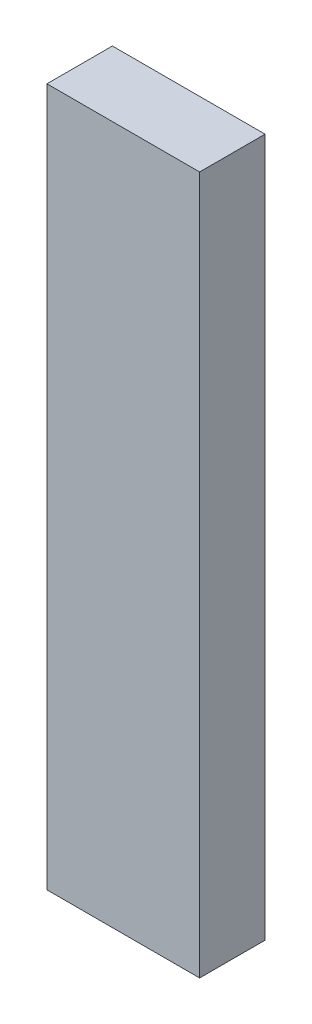
SolidWorks part; units mm, degrees
material "Pine"
ref_plane "Front Plane" through (0, 0, 0) normal (0, 0, 1) x (1, 0, 0)
ref_plane "Top Plane" through (0, 0, 0) normal (0, 1, 0) x (1, 0, 0)
ref_plane "Right Plane" through (0, 0, 0) normal (1, 0, 0) x (0, 0, -1)
sketch "Sketch1" plane through (0, 0, 0) normal (0, 1, 0) x (1, 0, 0)
  line L1 (0, 0) -> (88.9, 0)
  line L2 (0, 0) -> (0, 38.1)
  line L3 (0, 38.1) -> (88.9, 38.1)
  line L4 (88.9, 0) -> (88.9, 38.1)
  dimension "D1" = 88.9
  dimension "D2" = 38.1
extrude "Boss-Extrude1" add sketch "Sketch1" along normal blind 406.4
